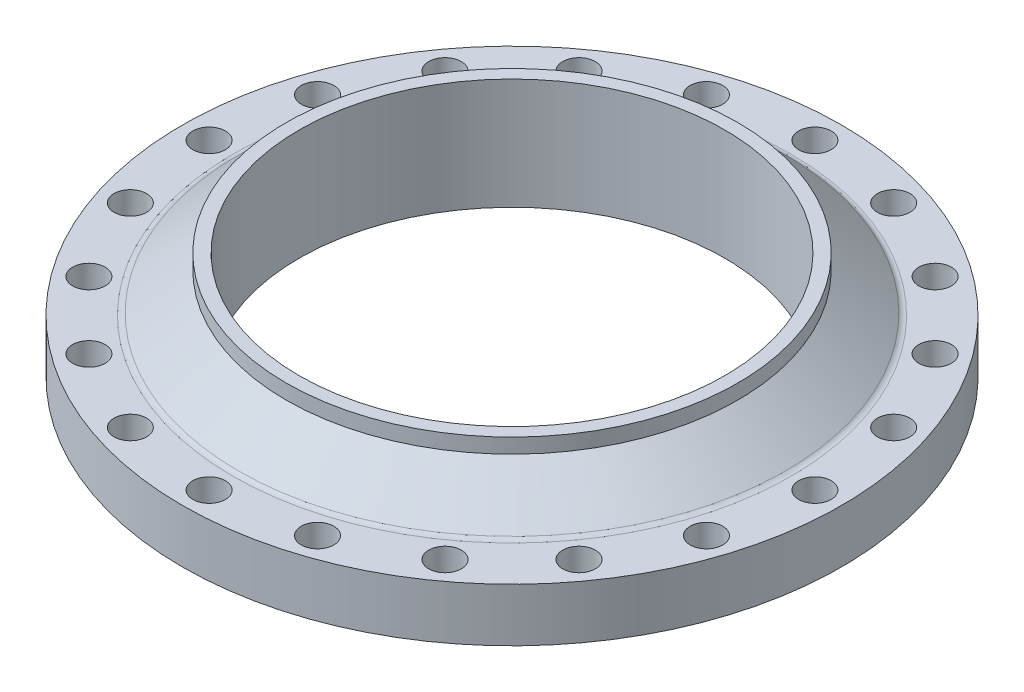
SolidWorks part; units mm, degrees
ref_plane "Front Plane" through (0, 0, 0) normal (0, 0, 1) x (1, 0, 0)
ref_plane "Top Plane" through (0, 0, 0) normal (0, 1, 0) x (1, 0, 0)
ref_plane "Right Plane" through (0, 0, 0) normal (1, 0, 0) x (0, 0, -1)
sketch "Sketch1" plane through (0, 0, 0) normal (0, 0, 1) x (1, 0, 0)
  line L0 (0, 163.8597) -> (0, 0) construction
  line L1 (287.4, 150) -> (287.4, 0)
  line L2 (287.4, 150) -> (304.8, 150)
  line L4 (376.7688, 77) -> (445, 77)
  line L5 (445, 77) -> (445, 5)
  line L6 (445, 5) -> (375, 5)
  line L7 (375, 5) -> (370, 0)
  line L8 (370, 0) -> (287.4, 0)
  line L9 (304.8, 150) -> (304.8, 130)
  line L10 (304.8, 130) -> (369.3809, 79.5439)
  arc A0 (369.3809, 79.5439) -> (376.7688, 77) centre (376.7688, 89) ccw
  dimension "D11" = 12
  dimension "D1" = 150
  dimension "D2" = 287.4
  dimension "D3" = 445
  dimension "D4" = 72
  dimension "D5" = 17.4
  dimension "D6" = 20
  dimension "D7" = 128
  dimension "D8" = 5
  dimension "D9" = 135
  dimension "D10" = 82.6
revolve "Revolve1" add sketch "Sketch1" angle 360 about L0
sketch "Sketch2" plane through (0, 5, 0) normal (0, -1, 0) x (1, 0, 0)
  circle A0 centre (0, 0) radius 409 construction
  circle A1 centre (0, 409) radius 22
  circle A2 centre (126.388, 388.9821) radius 22
  circle A3 centre (240.4042, 330.888) radius 22
  circle A4 centre (330.888, 240.4042) radius 22
  circle A5 centre (388.9821, 126.388) radius 22
  circle A6 centre (409, 0) radius 22
  circle A7 centre (388.9821, -126.388) radius 22
  circle A8 centre (330.888, -240.4042) radius 22
  circle A9 centre (240.4042, -330.888) radius 22
  circle A10 centre (126.388, -388.9821) radius 22
  circle A11 centre (0, -409) radius 22
  circle A12 centre (-126.388, -388.9821) radius 22
  circle A13 centre (-240.4042, -330.888) radius 22
  circle A14 centre (-330.888, -240.4042) radius 22
  circle A15 centre (-388.9821, -126.388) radius 22
  circle A16 centre (-409, 0) radius 22
  circle A17 centre (-388.9821, 126.388) radius 22
  circle A18 centre (-330.888, 240.4042) radius 22
  circle A19 centre (-240.4042, 330.888) radius 22
  circle A20 centre (-126.388, 388.9821) radius 22
  point P45 (0, 0)
  dimension "D1" = 44
  dimension "D2" = 20
extrude "Cut-Extrude1" cut sketch "Sketch2" against normal up to next
